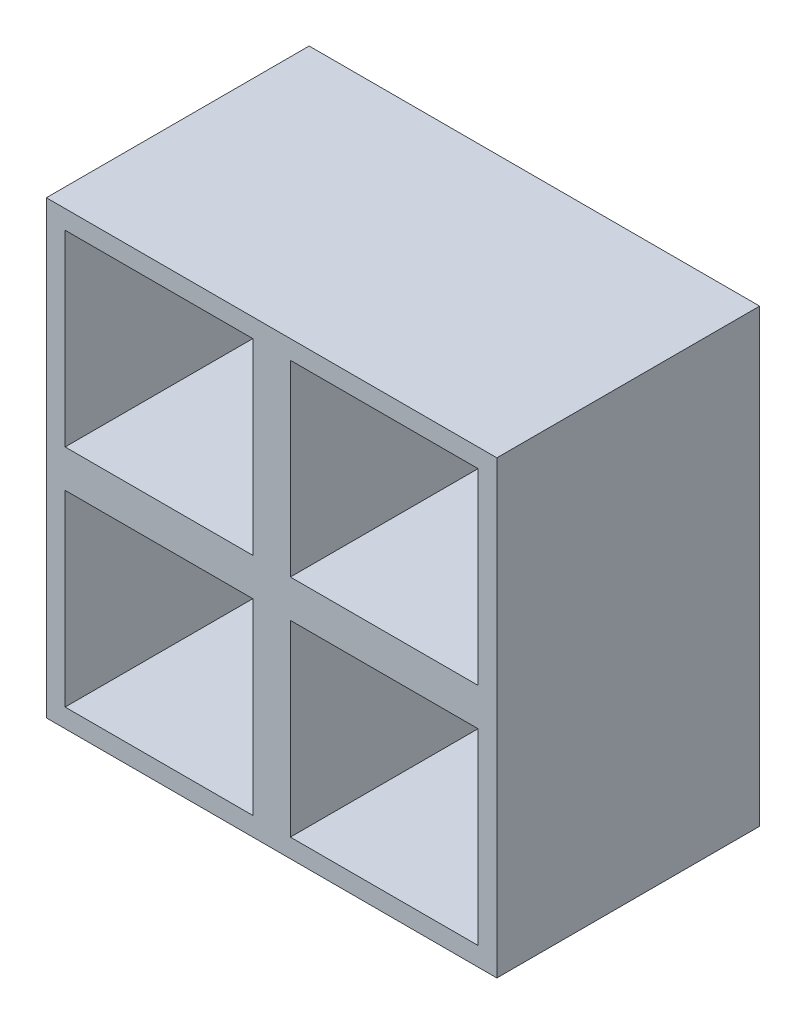
SolidWorks part; units mm, degrees
ref_plane "정면" through (0, 0, 0) normal (0, 0, 1) x (1, 0, 0)
ref_plane "윗면" through (0, 0, 0) normal (0, 1, 0) x (1, 0, 0)
ref_plane "우측면" through (0, 0, 0) normal (1, 0, 0) x (0, 0, -1)
sketch "스케치1" plane through (0, 0, 0) normal (0, 0, 1) x (1, 0, 0)
  line L1 (3, -3) -> (-3, -3)
  line L2 (3, -3) -> (3, 3)
  line L3 (3, 3) -> (-3, 3)
  line L4 (-3, -3) -> (-3, 3)
  line L5 (3, -3) -> (-3, 3) construction
  line L6 (3, 3) -> (-3, -3) construction
  point P0 (0, 0)
  dimension "D1" = 6
  dimension "D2" = 6
extrude "보스-돌출1" add sketch "스케치1" along normal blind 1
ref_plane "평면1" through (0, 0, 1) normal (0, 0, 1) x (1, 0, 0)
sketch "스케치2" plane through (0, 0, 1) normal (0, 0, 1) x (1, 0, 0)
  line L0 (0.25, 2.75) -> (0.25, 0.25)
  line L1 (3, -3) -> (-3, -3)
  line L3 (3, -3) -> (-3, -3)
  line L4 (-3, -3) -> (-3, 3)
  line L5 (3, -3) -> (-3, 3) construction
  line L6 (3, 3) -> (-3, -3) construction
  line L7 (2.75, 0.25) -> (2.75, 2.75)
  line L8 (3, -3) -> (3, 3)
  line L9 (0.25, -3) -> (-0.25, -3)
  line L10 (0.25, 0.25) -> (2.75, 0.25)
  line L11 (3, 3) -> (-3, 3)
  line L12 (-2.75, -0.25) -> (-0.25, -0.25)
  line L13 (-0.25, -0.25) -> (-0.25, -2.75)
  line L14 (2.75, -0.25) -> (0.25, -0.25)
  line L15 (0.25, -0.25) -> (0.25, -2.75)
  line L16 (-3, -3) -> (-3, 3)
  line L17 (3, -3) -> (-3, 3) construction
  line L18 (3, 3) -> (-3, -3) construction
  line L21 (-0.25, 0.25) -> (-2.75, 0.25)
  line L22 (-0.25, 0.25) -> (-0.25, 2.75)
  line L23 (-0.25, 2.75) -> (-2.75, 2.75)
  line L24 (-2.75, 0.25) -> (-2.75, 2.75)
  line L25 (0.25, 2.75) -> (2.75, 2.75)
  line L26 (2.75, -0.25) -> (2.75, -2.75)
  line L27 (0.25, -2.75) -> (2.75, -2.75)
  line L28 (-0.25, -2.75) -> (-2.75, -2.75)
  line L29 (-2.75, -0.25) -> (-2.75, -2.75)
  point P0 (0, 0)
  point P7 (0, 0)
  point P9 (0, 0)
  point P16 (0, 0)
extrude "보스-돌출2" add sketch "스케치2" along normal blind 2.5 contours L8 L11 L4 L1 L3 L29 L12 L13 L28 L27 L15 L14 L26 L21 L24 L23 L22 L0 L25 L7 L10
